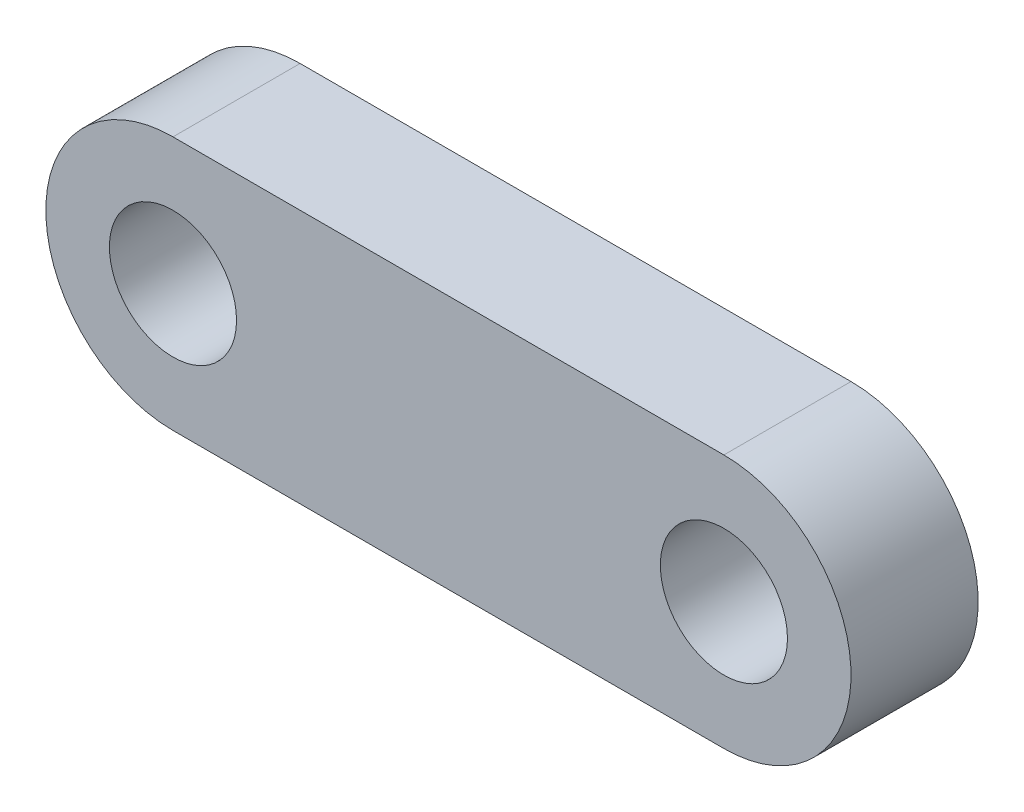
SolidWorks part; units mm, degrees
ref_plane "前视基准面" through (0, 0, 0) normal (0, 0, 1) x (1, 0, 0)
ref_plane "上视基准面" through (0, 0, 0) normal (0, 1, 0) x (1, 0, 0)
ref_plane "右视基准面" through (0, 0, 0) normal (1, 0, 0) x (0, 0, -1)
other "Configuration Table"
sketch "草图1" plane through (0, 0, 0) normal (0, 0, 1) x (1, 0, 0)
  line L0 (0, 0) -> (-13, 0) construction
  line L1 (0, -3) -> (-13, -3)
  line L2 (0, 3) -> (-13, 3)
  arc A0 (0, -3) -> (0, 3) centre (0, 0) ccw
  arc A1 (-13, 3) -> (-13, -3) centre (-13, 0) ccw
  circle A2 centre (-13, 0) radius 1.5
  circle A3 centre (0, 0) radius 1.5
  point P3 (-6.5, 0)
  dimension "D1" = 3
  dimension "D2" = 13
  dimension "D3" = 6
extrude "凸台-拉伸1" add sketch "草图1" along normal mid plane 3
